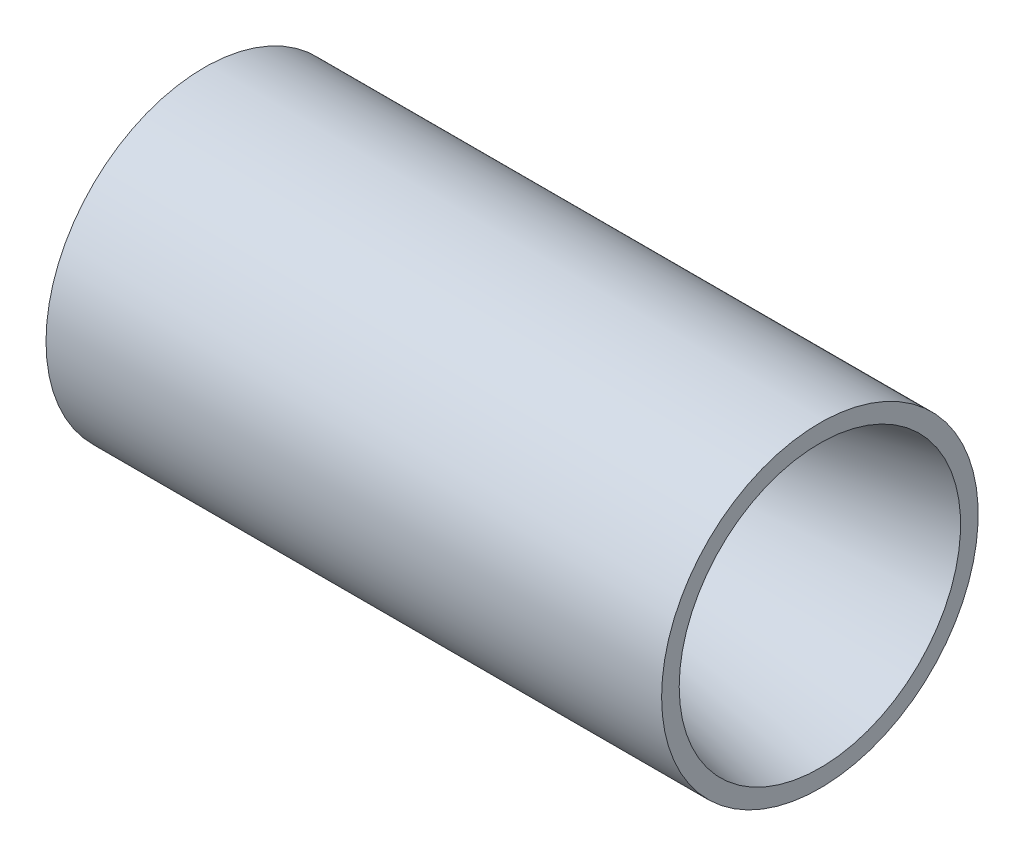
SolidWorks part; units mm, degrees
ref_plane "Спереди" through (0, 0, 0) normal (0, 0, 1) x (1, 0, 0)
ref_plane "Сверху" through (0, 0, 0) normal (0, 1, 0) x (1, 0, 0)
ref_plane "Справа" through (0, 0, 0) normal (1, 0, 0) x (0, 0, -1)
sketch "Эскиз1" plane through (0, 0, 0) normal (0, 0, 1) x (1, 0, 0)
  line L0 (0, 0) -> (57.277, 0) construction
  line L1 (0, 8) -> (0, 9)
  line L2 (0, 9) -> (35, 9)
  line L3 (35, 9) -> (35, 8)
  line L4 (35, 8) -> (10.6566, 3.1172)
  line L5 (6.2088, 3.968) -> (0, 8)
  arc A0 (10.6566, 3.1172) -> (6.2088, 3.968) centre (9.4766, 9) cw
  point P11 (35.1516, 0.8043)
  point P12 (8.0936, 5.9614)
  point P13 (21.7565, 3.578)
  point P14 (19.4794, 3.8482)
  point P15 (0, 0)
  point P16 (2.6674, 5.7618)
  point P17 (11.8352, 3.0535)
  point P18 (4.7839, 3.9858)
  point P19 (11.4434, 3.0494)
  point P20 (14.3446, 3.0792)
  point P21 (13.6853, 3.1296)
  point P22 (5.2789, 4.3037)
  point P23 (12.9711, 3.1124)
  point P24 (41.5142, 5.4926)
  point P25 (5.6917, 4.0146)
  point P26 (17.2022, 2.8805)
  dimension "D1" = 35
  dimension "D2" = 3
  dimension "D6" = 6
  dimension "D3" = 18
  dimension "D4" = 1
  dimension "D5" = 33
  dimension "D7" = 11.342
revolve "Повернуть1" add sketch "Эскиз1" angle 360 about L0
